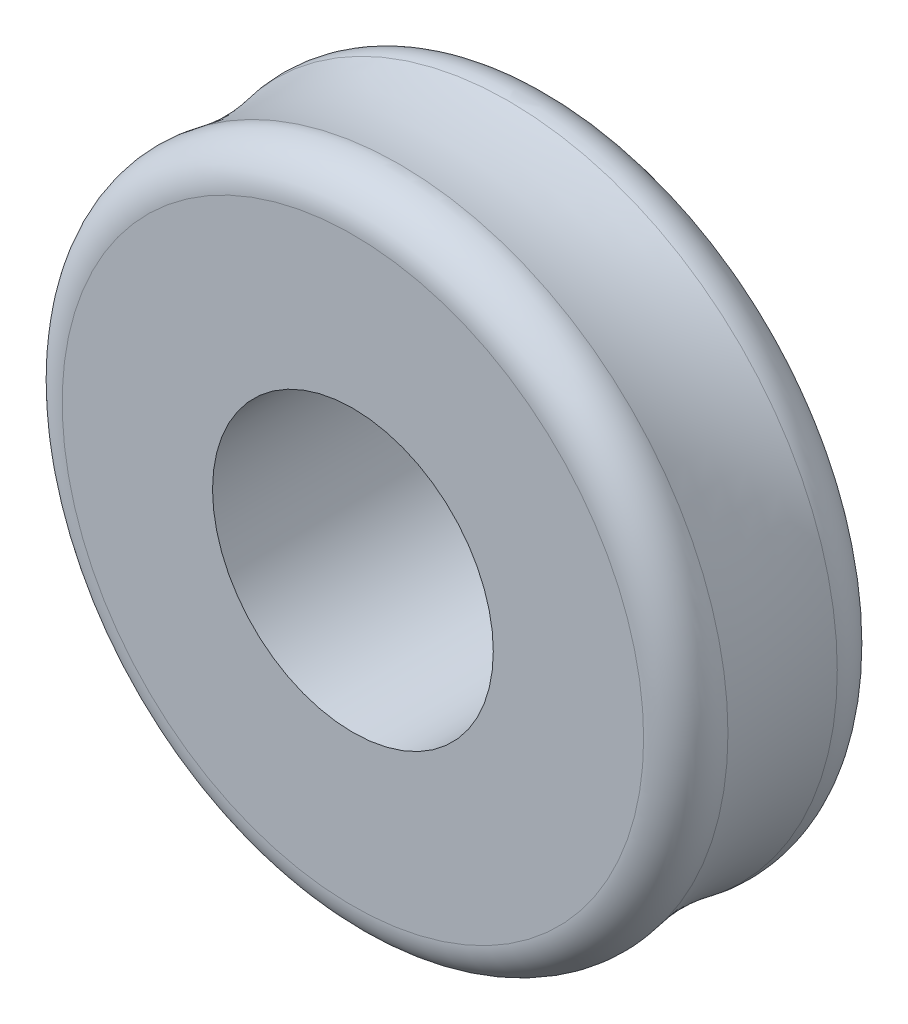
SolidWorks part; units mm, degrees
material "POLYURETHANE (11671)"
ref_plane "Front Plane" through (0, 0, 0) normal (0, 0, 1) x (1, 0, 0)
ref_plane "Top Plane" through (0, 0, 0) normal (0, 1, 0) x (1, 0, 0)
ref_plane "Right Plane" through (0, 0, 0) normal (1, 0, 0) x (0, 0, -1)
sketch "Sketch1" plane through (0, 0, 0) normal (0, 0, 1) x (1, 0, 0)
  circle A0 centre (0, 0) radius 4.4323
  circle A1 centre (0, 0) radius 1.8161
  dimension "D1" = 3.6322
  dimension "D2" = 8.8646
extrude "Boss-Extrude1" add sketch "Sketch1" along normal blind 2.6162
ref_axis "Central Axis" through (0, 0, 2.6162) along (0, 0, -1)
sketch "Sketch2" plane through (0, 0, 0) normal (1, 0, 0) x (0, 0, -1)
  line L0 (-2.6162, 4.4323) -> (0, 4.4323)
  arc A0 (0, 4.4323) -> (-2.6162, 4.4323) centre (-1.3081, 7.6787) cw
  dimension "D1" = 3.5
revolve "Cut-Revolve1" cut sketch "Sketch2" angle 360 about axis through (0, 0, 2.6162) along (0, 0, -1)
fillet "Fillet1" radius 0.5 2 edges at (4.4323, 0, 2.6162) (4.4323, 0, 0)
